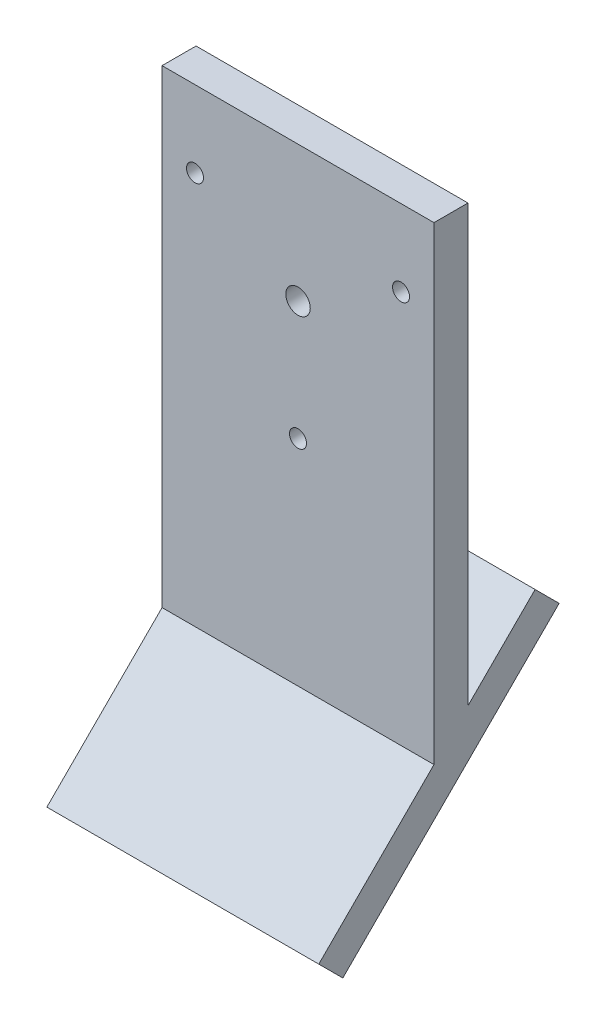
SolidWorks part; units mm, degrees
material "Polyether Polyol"
ref_plane "Front Plane" through (0, 0, 0) normal (0, 0, 1) x (1, 0, 0)
ref_plane "Top Plane" through (0, 0, 0) normal (0, 1, 0) x (1, 0, 0)
ref_plane "Right Plane" through (0, 0, 0) normal (1, 0, 0) x (0, 0, -1)
sketch "Sketch1" plane through (0, 0, 0) normal (1, 0, 0) x (0, 0, -1)
  line L0 (-15.9099, -15.9099) -> (15.9099, 15.9099)
  line L1 (15.9099, 15.9099) -> (12.3744, 19.4454)
  line L2 (12.3744, 19.4454) -> (2.5, 9.5711)
  line L3 (2.5, 9.5711) -> (2.5, 73.6134)
  line L4 (2.5, 73.6134) -> (-2.5, 73.6134)
  line L5 (-2.5, 73.6134) -> (-2.5, 4.5711)
  line L6 (-2.5, 4.5711) -> (-19.4454, -12.3744)
  line L7 (-19.4454, -12.3744) -> (-15.9099, -15.9099)
  line L8 (0, 0) -> (0, 73.6134) construction
  dimension "D1" = 45
  dimension "D2" = 45
  dimension "D3" = 5
  dimension "D4" = 5
  dimension "D5" = 54.1679
extrude "Boss-Extrude1" add sketch "Sketch1" along normal mid plane 40
hole_wizard "M3x0.5 Tapped Hole1" positions "Sketch2" profile "Sketch3" tap size "M3x0.5" standard "ANSI Metric" end condition up to next
sketch "Sketch2" plane through (0, 0, 2.5) normal (0, 0, 1) x (1, 0, 0)
  line L0 (-15.1554, 62.3634) -> (0, 53.6134) construction
  line L1 (0, 53.6134) -> (0, 36.1134) construction
  line L4 (15.1554, 62.3634) -> (0, 53.6134) construction
  line L7 (0, 53.6134) -> (-20, 53.6134) construction
  line L8 (-20, 73.6134) -> (-20, 4.5711) construction
  line L11 (0, 73.6134) -> (0, 53.6134) construction
  line L12 (20, 73.6134) -> (-20, 73.6134) construction
  circle A0 centre (0, 53.6134) radius 17.5 construction
  point P0 (-15.1554, 62.3634)
  point P2 (15.1554, 62.3634)
  point P4 (0, 36.1134)
  dimension "D2" = 35
  dimension "D1" = 120
sketch "Sketch3" plane through (-15.1554, 62.3634, 2.5) normal (1, 0, 0) x (0, -1, 0)
  line L0 (0, 0) -> (0, 5)
  line L1 (0, 5) -> (1.25, 5)
  line L2 (1.25, 5) -> (1.25, 0)
  line L5 (1.25, 0) -> (0, 0)
  line L11 (0, -6.35) -> (0, 107.95) construction
  dimension "Thru Tap Drill Dia." = 2.5
  dimension "Thru Tap Drill Depth" = 5
cosmetic thread "Hole Thread1"
cosmetic thread "Hole Thread2"
cosmetic thread "Hole Thread3"
hole_wizard "M3 Clearance Hole1" positions "Sketch4" profile "Sketch5" hole size "M3" standard "ANSI Metric" end condition up to next
sketch "Sketch4" plane through (0, 0, 2.5) normal (0, 0, 1) x (1, 0, 0)
  point P0 (0, 53.6134)
  point P2 (0, 53.6134)
sketch "Sketch5" plane through (0, 53.6134, 2.5) normal (1, 0, 0) x (0, -1, 0)
  line L0 (0, 0) -> (0, 5)
  line L1 (0, 5) -> (1.8, 5)
  line L2 (1.8, 5) -> (1.8, 0)
  line L5 (1.8, 0) -> (0, 0)
  line L11 (0, -6.35) -> (0, 107.95) construction
  dimension "Thru Hole Dia." = 3.6
  dimension "Thru Hole Depth" = 5
